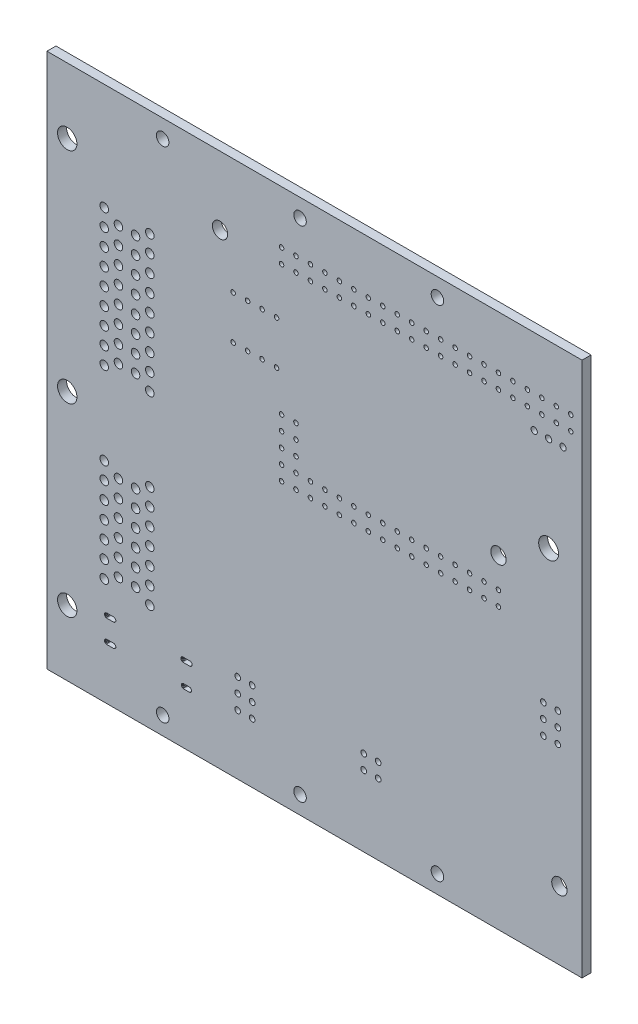
SolidWorks part; units mm, degrees
ref_plane "Front Plane" through (0, 0, 0) normal (0, 0, 1) x (1, 0, 0)
ref_plane "Top Plane" through (0, 0, 0) normal (0, 1, 0) x (1, 0, 0)
ref_plane "Right Plane" through (0, 0, 0) normal (1, 0, 0) x (0, 0, -1)
ref_plane "Plane1" through (0, 0, 1.58) normal (0, 0, 1) x (1, 0, 0)
sketch "Sketch1" plane through (0, 0, 1.58) normal (0, 0, 1) x (1, 0, 0)
  line L0 (58.0091, -126.0774) -> (58.0976, -126.1659)
  line L1 (58.0976, -126.1659) -> (58.1544, -126.2774)
  line L2 (58.1544, -126.2774) -> (58.174, -126.401)
  line L3 (58.174, -126.401) -> (58.1544, -126.5246)
  line L4 (58.1544, -126.5246) -> (58.0976, -126.6361)
  line L5 (58.0976, -126.6361) -> (58.0091, -126.7246)
  line L6 (58.0091, -126.7246) -> (57.8976, -126.7814)
  line L7 (57.8976, -126.7814) -> (57.774, -126.801)
  line L8 (57.774, -126.801) -> (56.574, -126.801)
  line L9 (56.574, -126.801) -> (56.4504, -126.7814)
  line L10 (56.4504, -126.7814) -> (56.3389, -126.7246)
  line L11 (56.3389, -126.7246) -> (56.2504, -126.6361)
  line L12 (56.2504, -126.6361) -> (56.1936, -126.5246)
  line L13 (56.1936, -126.5246) -> (56.174, -126.401)
  line L14 (56.174, -126.401) -> (56.1936, -126.2774)
  line L15 (56.1936, -126.2774) -> (56.2504, -126.1659)
  line L16 (56.2504, -126.1659) -> (56.3389, -126.0774)
  line L17 (56.3389, -126.0774) -> (56.4504, -126.0206)
  line L18 (56.4504, -126.0206) -> (56.574, -126.001)
  line L19 (56.574, -126.001) -> (57.774, -126.001)
  line L20 (57.774, -126.001) -> (57.8976, -126.0206)
  line L21 (57.8976, -126.0206) -> (58.0091, -126.0774)
  line L22 (58.0091, -130.0774) -> (58.0976, -130.1659)
  line L23 (58.0976, -130.1659) -> (58.1544, -130.2774)
  line L24 (58.1544, -130.2774) -> (58.174, -130.401)
  line L25 (58.174, -130.401) -> (58.1544, -130.5246)
  line L26 (58.1544, -130.5246) -> (58.0976, -130.6361)
  line L27 (58.0976, -130.6361) -> (58.0091, -130.7246)
  line L28 (58.0091, -130.7246) -> (57.8976, -130.7814)
  line L29 (57.8976, -130.7814) -> (57.774, -130.801)
  line L30 (57.774, -130.801) -> (56.574, -130.801)
  line L31 (56.574, -130.801) -> (56.4504, -130.7814)
  line L32 (56.4504, -130.7814) -> (56.3389, -130.7246)
  line L33 (56.3389, -130.7246) -> (56.2504, -130.6361)
  line L34 (56.2504, -130.6361) -> (56.1936, -130.5246)
  line L35 (56.1936, -130.5246) -> (56.174, -130.401)
  line L36 (56.174, -130.401) -> (56.1936, -130.2774)
  line L37 (56.1936, -130.2774) -> (56.2504, -130.1659)
  line L38 (56.2504, -130.1659) -> (56.3389, -130.0774)
  line L39 (56.3389, -130.0774) -> (56.4504, -130.0206)
  line L40 (56.4504, -130.0206) -> (56.574, -130.001)
  line L41 (56.574, -130.001) -> (57.774, -130.001)
  line L42 (57.774, -130.001) -> (57.8976, -130.0206)
  line L43 (57.8976, -130.0206) -> (58.0091, -130.0774)
  line L44 (71.4091, -126.0774) -> (71.4976, -126.1659)
  line L45 (71.4976, -126.1659) -> (71.5544, -126.2774)
  line L46 (71.5544, -126.2774) -> (71.574, -126.401)
  line L47 (71.574, -126.401) -> (71.5544, -126.5246)
  line L48 (71.5544, -126.5246) -> (71.4976, -126.6361)
  line L49 (71.4976, -126.6361) -> (71.4091, -126.7246)
  line L50 (71.4091, -126.7246) -> (71.2976, -126.7814)
  line L51 (71.2976, -126.7814) -> (71.174, -126.801)
  line L52 (71.174, -126.801) -> (69.974, -126.801)
  line L53 (69.974, -126.801) -> (69.8504, -126.7814)
  line L54 (69.8504, -126.7814) -> (69.7389, -126.7246)
  line L55 (69.7389, -126.7246) -> (69.6504, -126.6361)
  line L56 (69.6504, -126.6361) -> (69.5936, -126.5246)
  line L57 (69.5936, -126.5246) -> (69.574, -126.401)
  line L58 (69.574, -126.401) -> (69.5936, -126.2774)
  line L59 (69.5936, -126.2774) -> (69.6504, -126.1659)
  line L60 (69.6504, -126.1659) -> (69.7389, -126.0774)
  line L61 (69.7389, -126.0774) -> (69.8504, -126.0206)
  line L62 (69.8504, -126.0206) -> (69.974, -126.001)
  line L63 (69.974, -126.001) -> (71.174, -126.001)
  line L64 (71.174, -126.001) -> (71.2976, -126.0206)
  line L65 (71.2976, -126.0206) -> (71.4091, -126.0774)
  line L66 (71.3091, -130.0774) -> (71.3976, -130.1659)
  line L67 (71.3976, -130.1659) -> (71.4544, -130.2774)
  line L68 (71.4544, -130.2774) -> (71.474, -130.401)
  line L69 (71.474, -130.401) -> (71.4544, -130.5246)
  line L70 (71.4544, -130.5246) -> (71.3976, -130.6361)
  line L71 (71.3976, -130.6361) -> (71.3091, -130.7246)
  line L72 (71.3091, -130.7246) -> (71.1976, -130.7814)
  line L73 (71.1976, -130.7814) -> (71.074, -130.801)
  line L74 (71.074, -130.801) -> (70.074, -130.801)
  line L75 (70.074, -130.801) -> (69.9504, -130.7814)
  line L76 (69.9504, -130.7814) -> (69.8389, -130.7246)
  line L77 (69.8389, -130.7246) -> (69.7504, -130.6361)
  line L78 (69.7504, -130.6361) -> (69.6936, -130.5246)
  line L79 (69.6936, -130.5246) -> (69.674, -130.401)
  line L80 (69.674, -130.401) -> (69.6936, -130.2774)
  line L81 (69.6936, -130.2774) -> (69.7504, -130.1659)
  line L82 (69.7504, -130.1659) -> (69.8389, -130.0774)
  line L83 (69.8389, -130.0774) -> (69.9504, -130.0206)
  line L84 (69.9504, -130.0206) -> (70.074, -130.001)
  line L85 (70.074, -130.001) -> (71.074, -130.001)
  line L86 (71.074, -130.001) -> (71.1976, -130.0206)
  line L87 (71.1976, -130.0206) -> (71.3091, -130.0774)
  line L88 (140.054, -139.786) -> (140.054, -45.806)
  line L89 (140.054, -45.806) -> (46.074, -45.806)
  line L90 (46.074, -45.806) -> (46.074, -139.786)
  line L91 (46.074, -139.786) -> (140.054, -139.786)
  circle A0 centre (49.634, -57.296) radius 1.7
  circle A1 centre (66.394, -48.981) radius 1.1
  circle A2 centre (56.134, -64.546) radius 0.75
  circle A3 centre (56.134, -67.546) radius 0.75
  circle A4 centre (58.634, -66.046) radius 0.75
  circle A5 centre (56.134, -70.546) radius 0.75
  circle A6 centre (58.634, -69.046) radius 0.75
  circle A7 centre (64.134, -64.546) radius 0.75
  circle A8 centre (61.634, -66.046) radius 0.75
  circle A9 centre (64.134, -67.546) radius 0.75
  circle A10 centre (61.634, -69.046) radius 0.75
  circle A11 centre (64.134, -70.546) radius 0.75
  circle A12 centre (76.474, -57.806) radius 1.35
  circle A13 centre (90.524, -48.981) radius 1.1
  circle A14 centre (87.274, -55.066) radius 0.4
  circle A15 centre (87.274, -57.606) radius 0.4
  circle A16 centre (89.814, -55.066) radius 0.4
  circle A17 centre (92.354, -55.066) radius 0.4
  circle A18 centre (89.814, -57.606) radius 0.4
  circle A19 centre (92.354, -57.606) radius 0.4
  circle A20 centre (78.774, -66.1535) radius 0.4
  circle A21 centre (81.314, -66.1535) radius 0.4
  circle A22 centre (83.854, -66.1535) radius 0.4
  circle A23 centre (86.394, -66.1535) radius 0.4
  circle A24 centre (56.134, -73.546) radius 0.75
  circle A25 centre (58.634, -72.046) radius 0.75
  circle A26 centre (58.634, -75.046) radius 0.75
  circle A27 centre (56.134, -76.546) radius 0.75
  circle A28 centre (58.634, -78.046) radius 0.75
  circle A29 centre (56.134, -79.546) radius 0.75
  circle A30 centre (58.634, -81.046) radius 0.75
  circle A31 centre (61.634, -72.046) radius 0.75
  circle A32 centre (64.134, -73.546) radius 0.75
  circle A33 centre (61.634, -75.046) radius 0.75
  circle A34 centre (61.634, -78.046) radius 0.75
  circle A35 centre (64.134, -76.546) radius 0.75
  circle A36 centre (61.634, -81.046) radius 0.75
  circle A37 centre (64.134, -79.546) radius 0.75
  circle A38 centre (56.134, -82.546) radius 0.75
  circle A39 centre (58.634, -84.046) radius 0.75
  circle A40 centre (56.134, -85.546) radius 0.75
  circle A41 centre (58.634, -87.046) radius 0.75
  circle A42 centre (56.134, -88.546) radius 0.75
  circle A43 centre (61.634, -84.046) radius 0.75
  circle A44 centre (64.134, -82.546) radius 0.75
  circle A45 centre (61.634, -87.046) radius 0.75
  circle A46 centre (64.134, -85.546) radius 0.75
  circle A47 centre (64.134, -88.546) radius 0.75
  circle A48 centre (78.774, -73.7735) radius 0.4
  circle A49 centre (81.314, -73.7735) radius 0.4
  circle A50 centre (83.854, -73.7735) radius 0.4
  circle A51 centre (86.394, -73.7735) radius 0.4
  circle A52 centre (87.274, -80.466) radius 0.4
  circle A53 centre (89.814, -80.466) radius 0.4
  circle A54 centre (87.274, -83.006) radius 0.4
  circle A55 centre (87.274, -85.546) radius 0.4
  circle A56 centre (89.814, -83.006) radius 0.4
  circle A57 centre (89.814, -85.546) radius 0.4
  circle A58 centre (87.274, -88.086) radius 0.4
  circle A59 centre (87.274, -90.626) radius 0.4
  circle A60 centre (89.814, -88.086) radius 0.4
  circle A61 centre (92.354, -88.086) radius 0.4
  circle A62 centre (89.814, -90.626) radius 0.4
  circle A63 centre (92.354, -90.626) radius 0.4
  circle A64 centre (94.894, -55.066) radius 0.4
  circle A65 centre (97.434, -55.066) radius 0.4
  circle A66 centre (94.894, -57.606) radius 0.4
  circle A67 centre (97.434, -57.606) radius 0.4
  circle A68 centre (99.974, -55.066) radius 0.4
  circle A69 centre (102.514, -55.066) radius 0.4
  circle A70 centre (99.974, -57.606) radius 0.4
  circle A71 centre (102.514, -57.606) radius 0.4
  circle A72 centre (105.054, -55.066) radius 0.4
  circle A73 centre (107.594, -55.066) radius 0.4
  circle A74 centre (110.134, -55.066) radius 0.4
  circle A75 centre (105.054, -57.606) radius 0.4
  circle A76 centre (107.594, -57.606) radius 0.4
  circle A77 centre (110.134, -57.606) radius 0.4
  circle A78 centre (112.674, -55.066) radius 0.4
  circle A79 centre (115.214, -55.066) radius 0.4
  circle A80 centre (112.674, -57.606) radius 0.4
  circle A81 centre (115.214, -57.606) radius 0.4
  circle A82 centre (114.654, -48.981) radius 1.1
  circle A83 centre (117.754, -55.066) radius 0.4
  circle A84 centre (120.294, -55.066) radius 0.4
  circle A85 centre (117.754, -57.606) radius 0.4
  circle A86 centre (120.294, -57.606) radius 0.4
  circle A87 centre (122.834, -55.066) radius 0.4
  circle A88 centre (125.374, -55.066) radius 0.4
  circle A89 centre (122.834, -57.606) radius 0.4
  circle A90 centre (125.374, -57.606) radius 0.4
  circle A91 centre (127.914, -55.066) radius 0.4
  circle A92 centre (130.454, -55.066) radius 0.4
  circle A93 centre (127.914, -57.606) radius 0.4
  circle A94 centre (130.454, -57.606) radius 0.4
  circle A95 centre (132.994, -55.066) radius 0.4
  circle A96 centre (135.534, -55.066) radius 0.4
  circle A97 centre (138.074, -55.066) radius 0.4
  circle A98 centre (132.994, -57.606) radius 0.4
  circle A99 centre (135.534, -57.606) radius 0.4
  circle A100 centre (138.074, -57.606) radius 0.4
  circle A101 centre (131.644, -60.706) radius 0.55
  circle A102 centre (134.184, -60.706) radius 0.55
  circle A103 centre (136.724, -60.706) radius 0.55
  circle A104 centre (94.894, -88.086) radius 0.4
  circle A105 centre (97.434, -88.086) radius 0.4
  circle A106 centre (94.894, -90.626) radius 0.4
  circle A107 centre (97.434, -90.626) radius 0.4
  circle A108 centre (99.974, -88.086) radius 0.4
  circle A109 centre (102.514, -88.086) radius 0.4
  circle A110 centre (99.974, -90.626) radius 0.4
  circle A111 centre (102.514, -90.626) radius 0.4
  circle A112 centre (105.054, -88.086) radius 0.4
  circle A113 centre (107.594, -88.086) radius 0.4
  circle A114 centre (110.134, -88.086) radius 0.4
  circle A115 centre (105.054, -90.626) radius 0.4
  circle A116 centre (107.594, -90.626) radius 0.4
  circle A117 centre (110.134, -90.626) radius 0.4
  circle A118 centre (112.674, -88.086) radius 0.4
  circle A119 centre (115.214, -88.086) radius 0.4
  circle A120 centre (112.674, -90.626) radius 0.4
  circle A121 centre (115.214, -90.626) radius 0.4
  circle A122 centre (134.184, -77.366) radius 1.75
  circle A123 centre (125.374, -82.856) radius 1.35
  circle A124 centre (117.754, -88.086) radius 0.4
  circle A125 centre (120.294, -88.086) radius 0.4
  circle A126 centre (117.754, -90.626) radius 0.4
  circle A127 centre (120.294, -90.626) radius 0.4
  circle A128 centre (122.834, -88.086) radius 0.4
  circle A129 centre (125.374, -88.086) radius 0.4
  circle A130 centre (122.834, -90.626) radius 0.4
  circle A131 centre (125.374, -90.626) radius 0.4
  circle A132 centre (49.634, -95.796) radius 1.7
  circle A133 centre (56.134, -103.046) radius 0.75
  circle A134 centre (64.134, -103.046) radius 0.75
  circle A135 centre (56.134, -106.046) radius 0.75
  circle A136 centre (58.634, -104.546) radius 0.75
  circle A137 centre (56.134, -109.046) radius 0.75
  circle A138 centre (58.634, -107.546) radius 0.75
  circle A139 centre (58.634, -110.546) radius 0.75
  circle A140 centre (56.134, -112.046) radius 0.75
  circle A141 centre (58.634, -113.546) radius 0.75
  circle A142 centre (61.634, -104.546) radius 0.75
  circle A143 centre (64.134, -106.046) radius 0.75
  circle A144 centre (61.634, -107.546) radius 0.75
  circle A145 centre (64.134, -109.046) radius 0.75
  circle A146 centre (61.634, -110.546) radius 0.75
  circle A147 centre (61.634, -113.546) radius 0.75
  circle A148 centre (64.134, -112.046) radius 0.75
  circle A149 centre (56.134, -115.046) radius 0.75
  circle A150 centre (58.634, -116.546) radius 0.75
  circle A151 centre (56.134, -118.046) radius 0.75
  circle A152 centre (58.634, -119.546) radius 0.75
  circle A153 centre (56.134, -121.046) radius 0.75
  circle A154 centre (61.634, -116.546) radius 0.75
  circle A155 centre (64.134, -115.046) radius 0.75
  circle A156 centre (61.634, -119.546) radius 0.75
  circle A157 centre (64.134, -118.046) radius 0.75
  circle A158 centre (64.134, -121.046) radius 0.75
  circle A159 centre (49.634, -128.296) radius 1.7
  circle A160 centre (66.394, -136.631) radius 1.1
  circle A161 centre (79.574, -124.226) radius 0.5
  circle A162 centre (82.114, -124.226) radius 0.5
  circle A163 centre (79.574, -126.766) radius 0.5
  circle A164 centre (79.574, -129.306) radius 0.5
  circle A165 centre (82.114, -126.766) radius 0.5
  circle A166 centre (82.114, -129.306) radius 0.5
  circle A167 centre (90.524, -136.631) radius 1.1
  circle A168 centre (133.259, -101.251) radius 0.5
  circle A169 centre (133.259, -103.791) radius 0.5
  circle A170 centre (135.799, -101.251) radius 0.5
  circle A171 centre (135.799, -103.791) radius 0.5
  circle A172 centre (133.259, -106.331) radius 0.5
  circle A173 centre (135.799, -106.331) radius 0.5
  circle A174 centre (101.709, -124.806) radius 0.5
  circle A175 centre (104.249, -124.806) radius 0.5
  circle A176 centre (101.709, -127.346) radius 0.5
  circle A177 centre (104.249, -127.346) radius 0.5
  circle A178 centre (114.654, -136.631) radius 1.1
  circle A179 centre (136.074, -127.806) radius 1.35
  dimension "D1" = 3.175
  dimension "D2" = 3.155
  dimension "D3" = 93.98
  dimension "D4" = 93.98
  dimension "D5" = 20.32
  dimension "D6" = 20.32
extrude "Boss-Extrude1" add sketch "Sketch1" against normal blind 1.58
